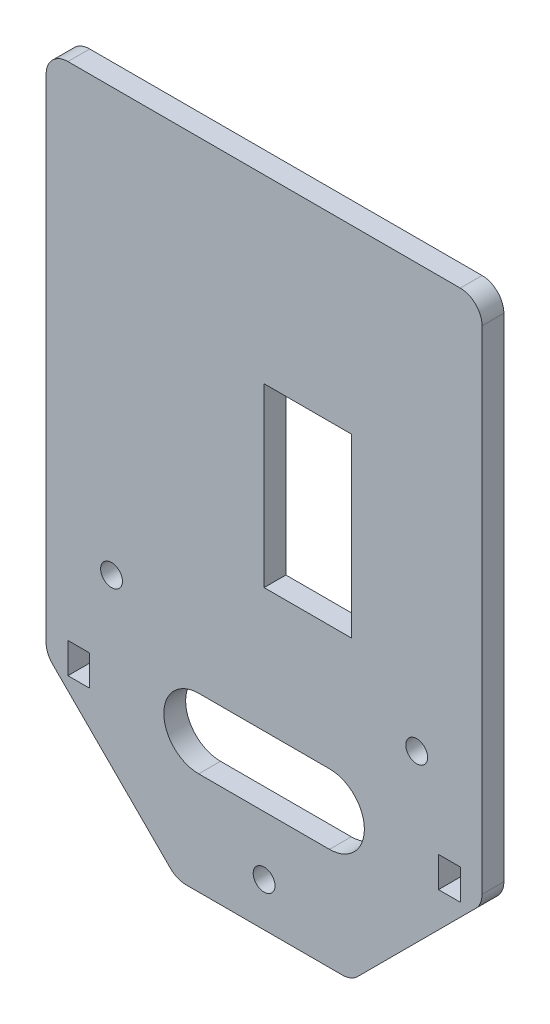
SolidWorks part; units mm, degrees
ref_plane "Front Plane" through (0, 0, 0) normal (0, 0, 1) x (1, 0, 0)
ref_plane "Top Plane" through (0, 0, 0) normal (0, 1, 0) x (1, 0, 0)
ref_plane "Right Plane" through (0, 0, 0) normal (1, 0, 0) x (0, 0, -1)
sketch "Sketch1" plane through (0, 0, 0) normal (0, 0, 1) x (1, 0, 0)
  line L0 (0, 40) -> (30, 10)
  line L1 (30, 10) -> (70, 10)
  line L2 (0, 40) -> (0, 160)
  line L3 (0, 160) -> (100, 160)
  line L4 (100, 40) -> (100, 160)
  line L5 (100, 40) -> (70, 10)
  dimension "D3" = 30
  dimension "D4" = 30
  dimension "D5" = 100
  dimension "D1" = 30
  dimension "D2" = 30
  dimension "D6" = 120
extrude "Boss-Extrude1" add sketch "Sketch1" along normal blind 5
sketch "Sketch3" plane through (0, 0, 5) normal (0, 0, 1) x (1, 0, 0)
  line L0 (50, 78) -> (70, 78)
  line L1 (50, 78) -> (50, 118.5)
  line L2 (50, 118.5) -> (70, 118.5)
  line L3 (70, 78) -> (70, 118.5)
  line L4 (30, 10) -> (70, 10) construction
  line L5 (0, 160) -> (0, 40) construction
  line L8 (100, 40) -> (100, 160) construction
  line L9 (35, 41.5) -> (65, 41.5) construction
  line L10 (35, 49.5) -> (65, 49.5)
  line L11 (35, 33.5) -> (65, 33.5)
  circle A0 centre (50, 20) radius 2.5
  circle A1 centre (85, 63) radius 2.5
  circle A2 centre (15, 63) radius 2.5
  arc A3 (35, 49.5) -> (35, 33.5) centre (35, 41.5) ccw
  arc A4 (65, 33.5) -> (65, 49.5) centre (65, 41.5) ccw
  point P16 (50, 41.5)
  dimension "D1" = 5
  dimension "D2" = 5
  dimension "D3" = 5
  dimension "D17" = 8
  dimension "D4" = 43
  dimension "D5" = 43
  dimension "D6" = 35
  dimension "D7" = 20
  dimension "D8" = 40.5
  dimension "D9" = 15
  dimension "D10" = 30
  dimension "D11" = 68
  dimension "D12" = 15
  dimension "D13" = 35
  dimension "D14" = 30
  dimension "D15" = 15
  dimension "D16" = 21.5
extrude "Cut-Extrude3" cut sketch "Sketch3" against normal through all
fillet "Fillet1" radius 5 1 edges at (0, 40, 2.5)
fillet "Fillet2" radius 5 1 edges at (100, 40, 2.5)
fillet "Fillet3" radius 5 1 edges at (70, 10, 2.5)
fillet "Fillet4" radius 5 1 edges at (30, 10, 2.5)
fillet "Fillet5" radius 5 1 edges at (100, 160, 2.5)
fillet "Fillet6" radius 5 1 edges at (0, 160, 2.5)
sketch "Sketch4" plane through (0, 0, 5) normal (0, 0, 1) x (1, 0, 0)
  line L0 (65, 49.5) -> (35, 49.5) construction
  line L1 (5, 45) -> (10, 45)
  line L2 (5, 45) -> (5, 38)
  line L3 (5, 38) -> (10, 38)
  line L4 (10, 45) -> (10, 38)
  line L5 (90, 45) -> (95, 45)
  line L6 (90, 45) -> (90, 38)
  line L7 (90, 38) -> (95, 38)
  line L8 (95, 45) -> (95, 38)
  line L9 (0, 155) -> (0, 42.0711) construction
  line L10 (100, 42.0711) -> (100, 155) construction
  dimension "D1" = 5
  dimension "D2" = 7
  dimension "D3" = 5
  dimension "D4" = 7
  dimension "D5" = 4.5
  dimension "D6" = 5
  dimension "D7" = 5
  dimension "D8" = 4.5
extrude "Cut-Extrude6" cut sketch "Sketch4" against normal through all
